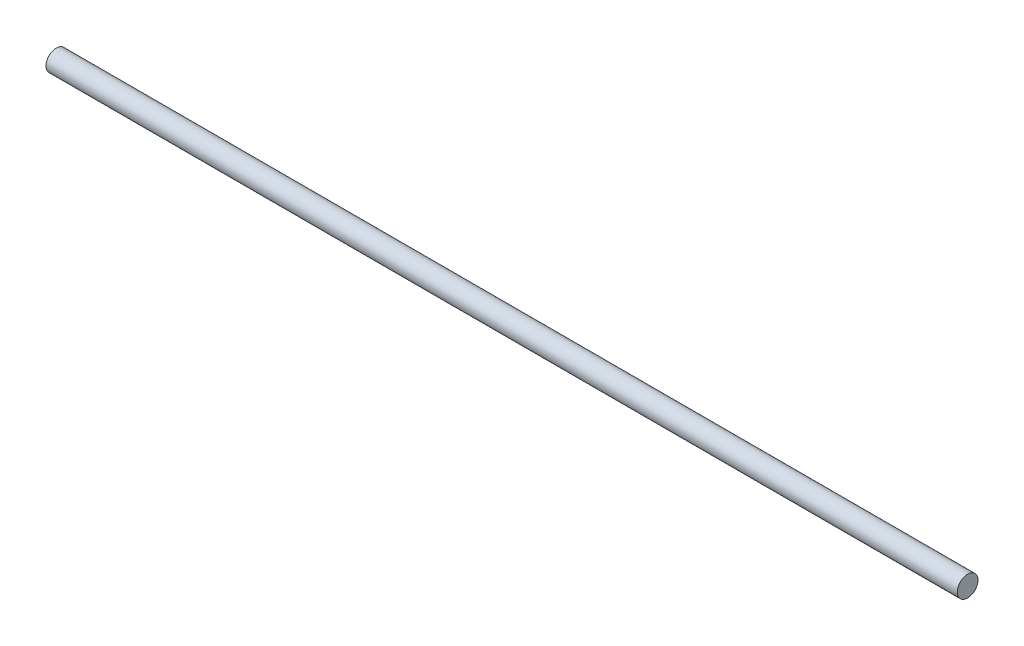
SolidWorks part; units mm, degrees
ref_plane "Front Plane" through (0, 0, 0) normal (0, 0, 1) x (1, 0, 0)
ref_plane "Top Plane" through (0, 0, 0) normal (0, 1, 0) x (1, 0, 0)
ref_plane "Right Plane" through (0, 0, 0) normal (1, 0, 0) x (0, 0, -1)
sketch "Sketch3" plane through (0, 0, 0) normal (1, 0, 0) x (0, 0, -1)
  circle A0 centre (-0.3583, 0.2483) radius 5
extrude "Boss-Extrude1" add sketch "Sketch3" along normal blind 440
